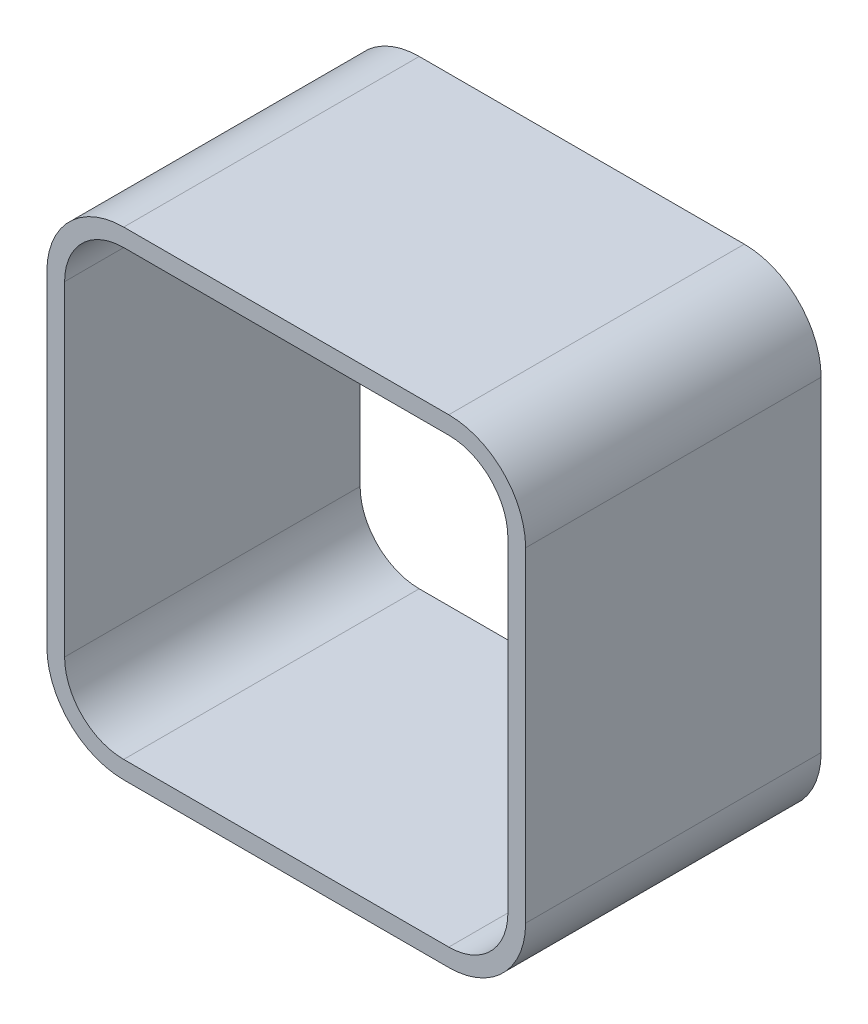
SolidWorks part; units mm, degrees
ref_plane "Front Plane" through (0, 0, 0) normal (0, 0, 1) x (1, 0, 0)
ref_plane "Top Plane" through (0, 0, 0) normal (0, 1, 0) x (1, 0, 0)
ref_plane "Right Plane" through (0, 0, 0) normal (1, 0, 0) x (0, 0, -1)
sketch "Sketch1" plane through (0, 0, 0) normal (0, 0, 1) x (1, 0, 0)
  line L1 (-7.5, 7.5) -> (7.5, 7.5)
  line L2 (-7.5, 7.5) -> (-7.5, -7.5)
  line L3 (-7.5, -7.5) -> (7.5, -7.5)
  line L4 (7.5, 7.5) -> (7.5, -7.5)
  line L5 (-7.5, 7.5) -> (7.5, -7.5) construction
  line L6 (-7.5, -7.5) -> (7.5, 7.5) construction
  line L7 (-8.1, 8.1) -> (8.1, 8.1)
  line L8 (-8.1, 8.1) -> (-8.1, -8.1)
  line L9 (-8.1, -8.1) -> (8.1, -8.1)
  line L10 (8.1, 8.1) -> (8.1, -8.1)
  line L11 (-8.1, 8.1) -> (8.1, -8.1) construction
  line L12 (-8.1, -8.1) -> (8.1, 8.1) construction
  point P0 (0, 0)
  point P7 (0, 0)
  dimension "D1" = 0.6
  dimension "D2" = 0.6
  dimension "D3" = 15
  dimension "D4" = 15
extrude "Boss-Extrude1" add sketch "Sketch1" along normal blind 10
fillet "Fillet1" radius 2 4 edges at (-7.5, -7.5, 5) (7.5, -7.5, 5) (7.5, 7.5, 5) (-7.5, 7.5, 5)
fillet "Fillet2" radius 2.6 4 edges at (8.1, -8.1, 5) (8.1, 8.1, 5) (-8.1, -8.1, 5) (-8.1, 8.1, 5)
equation "\"D3@Sketch1\"=\"D4@Sketch1\""
